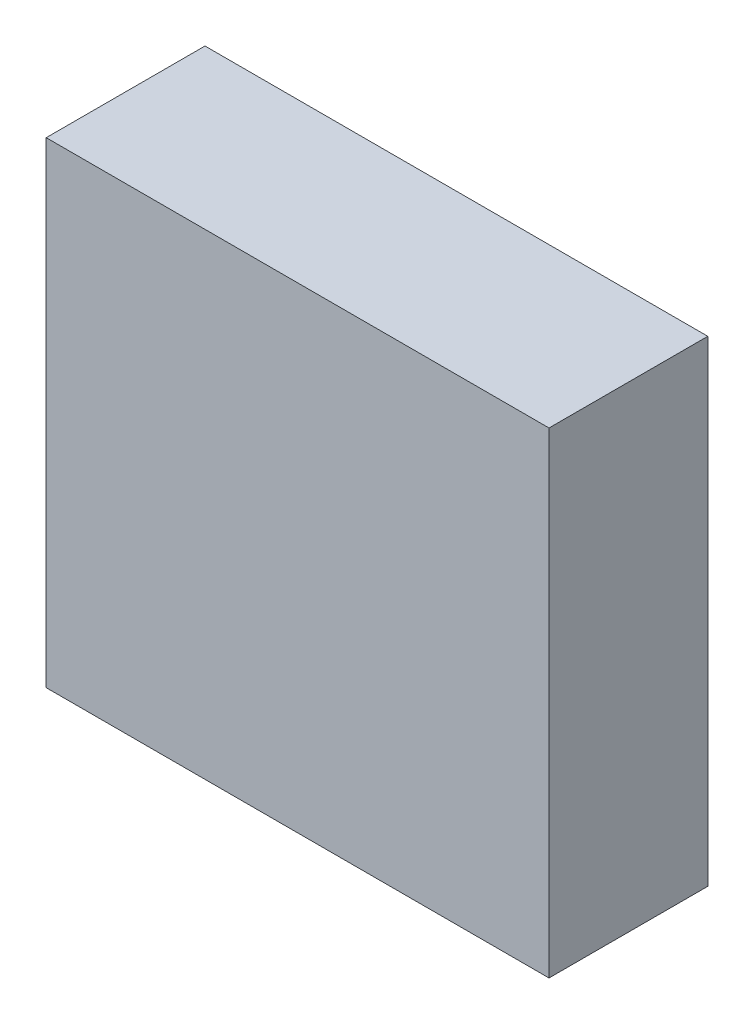
SolidWorks part; units mm, degrees
ref_plane "Front Plane" through (0, 0, 0) normal (0, 0, 1) x (1, 0, 0)
ref_plane "Top Plane" through (0, 0, 0) normal (0, 1, 0) x (1, 0, 0)
ref_plane "Right Plane" through (0, 0, 0) normal (1, 0, 0) x (0, 0, -1)
sketch "Sketch1" plane through (0, 0, 0) normal (0, 0, 1) x (1, 0, 0)
  line L1 (-47.5, 45) -> (47.5, 45)
  line L2 (-47.5, 45) -> (-47.5, -45)
  line L3 (-47.5, -45) -> (47.5, -45)
  line L4 (47.5, 45) -> (47.5, -45)
  line L5 (-47.5, 45) -> (47.5, -45) construction
  line L6 (-47.5, -45) -> (47.5, 45) construction
  point P0 (0, 0)
  dimension "D1" = 95
  dimension "D2" = 90
extrude "Boss-Extrude1" add sketch "Sketch1" along normal blind 30
